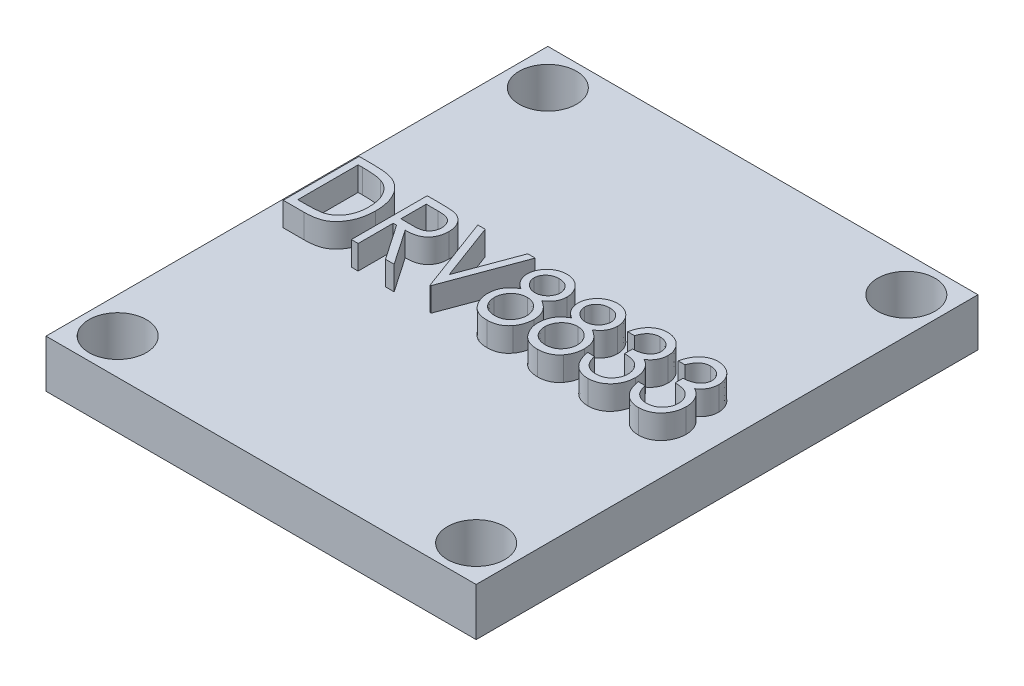
SolidWorks part; units mm, degrees
ref_plane "Front Plane" through (0, 0, 0) normal (0, 0, 1) x (1, 0, 0)
ref_plane "Top Plane" through (0, 0, 0) normal (0, 1, 0) x (1, 0, 0)
ref_plane "Right Plane" through (0, 0, 0) normal (1, 0, 0) x (0, 0, -1)
sketch "Sketch1" plane through (0, 0, 0) normal (0, 1, 0) x (1, 0, 0)
  line L1 (-9, -10.5) -> (9, -10.5)
  line L2 (-9, -10.5) -> (-9, 10.5)
  line L3 (-9, 10.5) -> (9, 10.5)
  line L4 (9, -10.5) -> (9, 10.5)
  line L5 (-9, -10.5) -> (9, 10.5) construction
  line L6 (-9, 10.5) -> (9, -10.5) construction
  circle A0 centre (-7.5, 9) radius 1.2
  circle A1 centre (7.5, 9) radius 1.2
  circle A2 centre (-7.5, -9) radius 1.2
  circle A3 centre (7.5, -9) radius 1.2
  point P0 (0, 0)
  dimension "D3" = 2.4
  dimension "D1" = 18
  dimension "D2" = 21
  dimension "D7" = 1.5
  dimension "D8" = 1.5
  dimension "D9" = 0
  dimension "D10" = 1.5
  dimension "D11" = 0
  dimension "D12" = 1.5
  dimension "D13" = 0
  dimension "D14" = 0
extrude "Boss-Extrude1" add sketch "Sketch1" along normal blind 2 contours L3 L4 L1 L2 | A1 | A2 | A3 | A0
sketch "Sketch3" plane through (0, 2, 0) normal (0, 1, 0) x (1, 0, 0)
  text T0 "DRV8833" font "Century Gothic" height 3.175
  point P1 (-6.9907, -2.1672)
  point P2 (-7.7175, -2.1408)
  point P3 (-7.691, -1.5329)
  point P4 (-8.1139, -1.5858)
  point P5 (-8.5897, -1.599)
  point P6 (0, 0)
  point P7 (-8.2857, -1.6122)
extrude "Boss-Extrude2" add sketch "Sketch3" along normal blind 1
